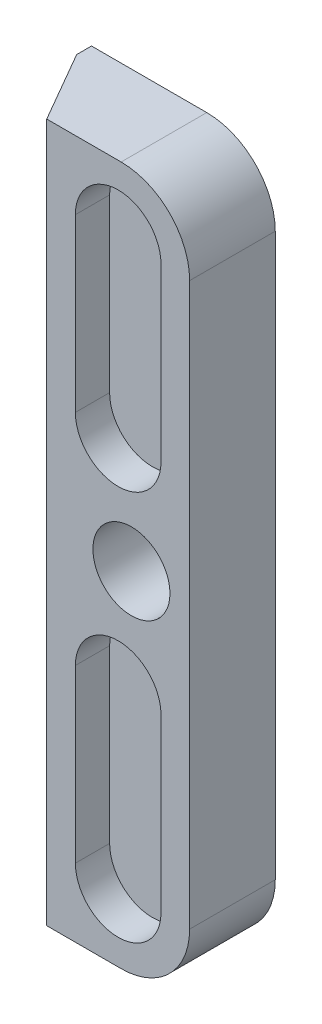
SolidWorks part; units mm, degrees
material "Сплав 2024"
ref_plane "Спереди" through (0, 0, 0) normal (0, 0, 1) x (1, 0, 0)
ref_plane "Сверху" through (0, 0, 0) normal (0, 1, 0) x (1, 0, 0)
ref_plane "Справа" through (0, 0, 0) normal (1, 0, 0) x (0, 0, -1)
sketch "Эскиз1" plane through (0, 0, 0) normal (0, 1, 0) x (1, 0, 0)
  line L0 (0, 0) -> (0, 5)
  line L1 (0, 5) -> (-11.2321, 5)
  line L2 (0, 0) -> (-8.3453, 0)
  line L3 (-8.3453, 0) -> (-11.2321, 5)
  line L4 (-9.5, 2) -> (-9.5, 0) construction
  line L5 (-8.3453, 0) -> (-9.4483, 0) construction
  dimension "D1" = 2
  dimension "D2" = 60
  dimension "D3" = 5
  dimension "D4" = 9.5
extrude "Бобышка-Вытянуть1" add sketch "Эскиз1" along normal blind 40.8
fillet "Скругление1" radius 4 2 edges at (0, 0, -2.5) (0, 40.8, -2.5)
sketch "Эскиз4" plane through (0, 0, 0) normal (0, 0, 1) x (1, 0, 0)
  line L0 (0, 20.4) -> (-8.3453, 20.4) construction
  line L1 (0, 36.8) -> (0, 4) construction
  line L2 (-8.3453, 40.8) -> (-8.3453, 0) construction
  line L3 (-4.1726, 20.4) -> (-4.1726, 33.5057) construction
  line L4 (-4.1726, 36.8) -> (-4.1726, 26.8) construction
  line L5 (-1.6726, 36.8) -> (-1.6726, 26.8)
  line L6 (-6.6726, 36.8) -> (-6.6726, 26.8)
  line L7 (-8.3453, 40.8) -> (-4, 40.8) construction
  line L8 (-4.1726, 4) -> (-4.1726, 14) construction
  line L9 (-1.6726, 4) -> (-1.6726, 14)
  line L10 (-6.6726, 4) -> (-6.6726, 14)
  arc A0 (-1.6726, 36.8) -> (-6.6726, 36.8) centre (-4.1726, 36.8) ccw
  arc A1 (-6.6726, 26.8) -> (-1.6726, 26.8) centre (-4.1726, 26.8) ccw
  arc A2 (-1.6726, 4) -> (-6.6726, 4) centre (-4.1726, 4) cw
  arc A3 (-6.6726, 14) -> (-1.6726, 14) centre (-4.1726, 14) cw
  point P10 (-4.1726, 31.8)
  point P19 (-4.1726, 9)
  dimension "D1" = 10
  dimension "D2" = 5
  dimension "D3" = 4
extrude "Вырез-Вытянуть1" cut sketch "Эскиз4" against normal offset from surface (2 mm away) 3 up to face at (-4.8012, 20.4, -5)
sketch "Эскиз5" plane through (0, 0, 0) normal (0, 0, 1) x (1, 0, 0)
  line L0 (0, 20.4) -> (-5.6917, 20.4) construction
  line L1 (0, 36.8) -> (0, 4) construction
  point P4 (-3.4, 20.4)
  dimension "D1" = 3.4
hole_wizard "Отверстие с зазором M41" positions "Эскиз7" profile "Эскиз6" hole size "M4" standard "Ansi Metric" end condition through all
sketch "Эскиз7" plane through (0, 0, 0) normal (0, 0, 1) x (1, 0, 0)
  point P0 (-3.4, 20.4)
sketch "Эскиз6" plane through (-3.4, 20.4, 0) normal (1, 0, 0) x (0, -1, 0)
  line L0 (0, 0) -> (0, 5)
  line L1 (0, 5) -> (2.25, 5)
  line L2 (2.25, 5) -> (2.25, 0)
  line L5 (2.25, 0) -> (0, 0)
  line L11 (0, -6.35) -> (0, 107.95) construction
  dimension "Диаметр сквозного отверстия" = 4.5
  dimension "Глубина сквозного отверстия" = 5
chamfer "Фаска1" distance 0.5 angle 90 1 edges at (-11.2321, 20.4, -5)
